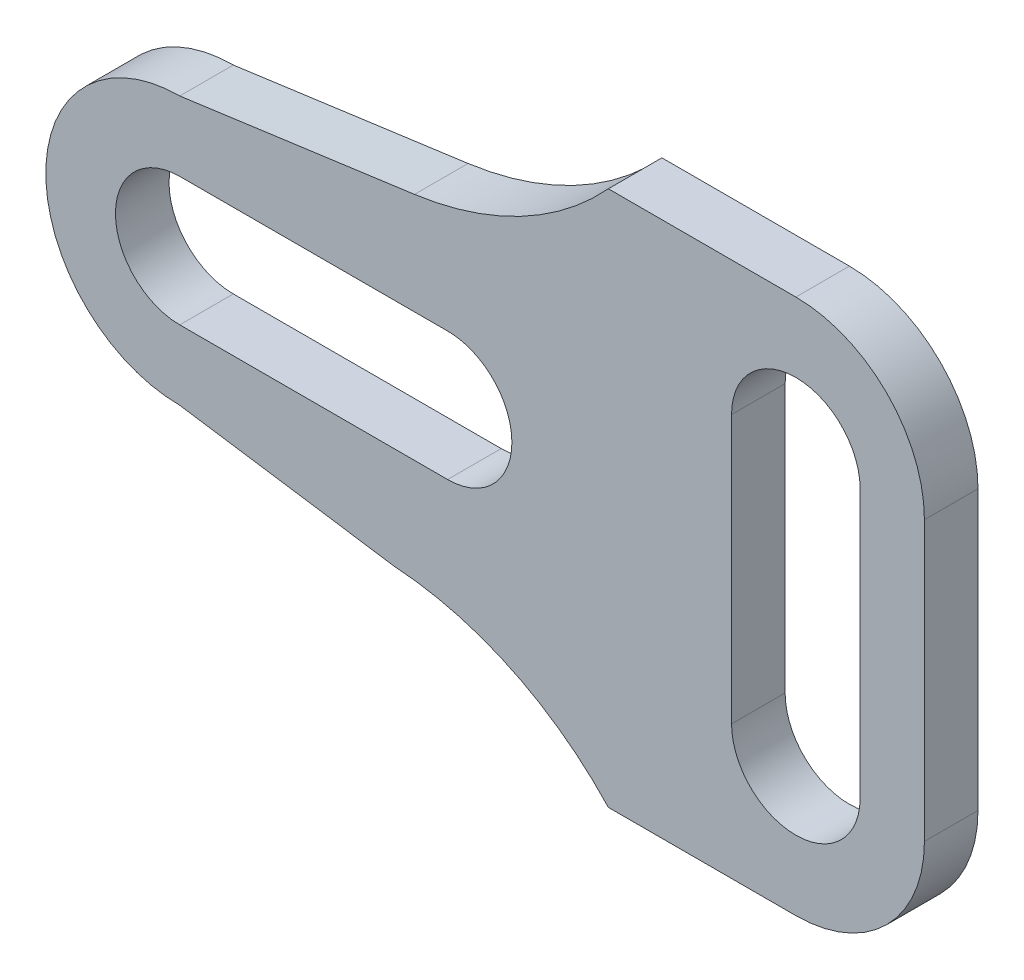
SolidWorks part; units mm, degrees
ref_plane "Front Plane" through (0, 0, 0) normal (0, 0, 1) x (1, 0, 0)
ref_plane "Top Plane" through (0, 0, 0) normal (0, 1, 0) x (1, 0, 0)
ref_plane "Right Plane" through (0, 0, 0) normal (1, 0, 0) x (0, 0, -1)
sketch "Sketch1" plane through (0, 0, 0) normal (0, 0, 1) x (1, 0, 0)
  line L0 (0, 228.5435) -> (0, -21.4565) construction
  line L1 (60, 228.5435) -> (60, -21.4565)
  line L2 (-60, 228.5435) -> (-60, -21.4565)
  line L3 (-175, 353.5435) -> (0, 353.5435)
  line L4 (120, 233.5435) -> (120, -26.4565)
  line L5 (0, -146.4565) -> (-175, -146.4565)
  line L6 (-325, 103.5435) -> (-575, 103.5435) construction
  line L7 (-325, 43.5435) -> (-575, 43.5435)
  line L8 (-325, 163.5435) -> (-575, 163.5435)
  line L12 (-575, -21.4565) -> (-375, -51.4565)
  line L15 (-575, 228.5435) -> (-355.8979, 258.5435)
  arc A0 (60, 228.5435) -> (-60, 228.5435) centre (0, 228.5435) ccw
  arc A1 (-60, -21.4565) -> (60, -21.4565) centre (0, -21.4565) ccw
  arc A2 (0, -146.4565) -> (120, -26.4565) centre (0, -26.4565) ccw
  arc A3 (120, 233.5435) -> (0, 353.5435) centre (0, 233.5435) ccw
  arc A4 (-325, 43.5435) -> (-325, 163.5435) centre (-325, 103.5435) ccw
  arc A5 (-575, 163.5435) -> (-575, 43.5435) centre (-575, 103.5435) ccw
  arc A6 (-575, 228.5435) -> (-575, -21.4565) centre (-575, 103.5435) ccw
  arc A8 (-375, -51.4565) -> (-175, -146.4565) centre (-394.6321, -350.8135) cw
  arc A10 (-355.8979, 258.5435) -> (-175, 353.5435) centre (-396.595, 555.7702) ccw
  point P3 (0, 103.5435)
  point P18 (-450, 103.5435)
  dimension "D2" = 60
  dimension "D3" = 120
  dimension "D8" = 60
  dimension "D10" = 95
  dimension "D11" = 300
  dimension "D12" = 125
  dimension "D15" = 250
  dimension "D13" = 300
  dimension "D1" = 125
  dimension "D4" = 175
  dimension "D5" = 175
  dimension "D6" = 175
  dimension "D7" = 125
  dimension "D9" = 575
  dimension "D14" = 200
  dimension "D16" = 250
  dimension "D18" = 95
extrude "Boss-Extrude1" add sketch "Sketch1" along normal blind 50
